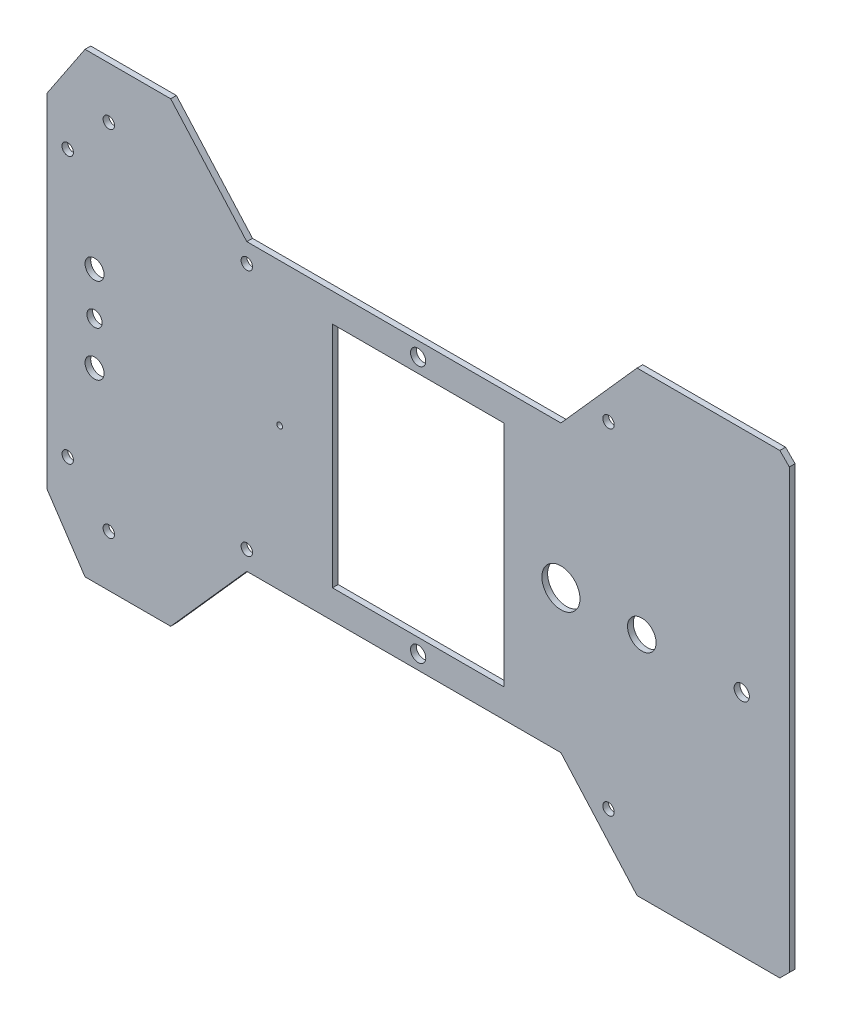
SolidWorks part; units mm, degrees
ref_plane "前视基准面" through (0, 0, 0) normal (0, 0, 1) x (1, 0, 0)
ref_plane "上视基准面" through (0, 0, 0) normal (0, 1, 0) x (1, 0, 0)
ref_plane "右视基准面" through (0, 0, 0) normal (1, 0, 0) x (0, 0, -1)
other "Configuration Table"
sketch "草图1" plane through (0, 0, 0) normal (0, 0, 1) x (1, 0, 0)
  line L0 (0, 0) -> (177289.5009, 0) construction
  line L1 (195, 115) -> (190, 115)
  line L2 (190, 115) -> (190, 120)
  line L3 (0, 0) -> (0, 177289.5009) construction
  line L4 (-175, 120) -> (-175, 90)
  line L5 (-195, 120) -> (195, 120)
  line L6 (-195, 120) -> (-195, -120)
  line L7 (-195, -120) -> (195, -120)
  line L8 (195, 120) -> (195, -120)
  line L9 (-45, 60) -> (45, 60)
  line L10 (-45, 60) -> (-45, -60)
  line L11 (-45, -60) -> (45, -60)
  line L12 (45, 60) -> (45, -60)
  line L13 (-175, 90) -> (-195, 90)
  line L14 (-175, 120) -> (-195, 90)
  line L15 (-175, 120) -> (-130, 120)
  line L16 (190, 120) -> (195, 115)
  line L17 (190, 120) -> (115, 120)
  line L18 (115, 120) -> (115, 75)
  line L19 (115, 75) -> (75, 75)
  line L20 (-130, 120) -> (-130, 75)
  line L21 (-130, 75) -> (-90, 75)
  line L22 (-130, 120) -> (-90, 75)
  line L23 (115, 120) -> (75, 75)
  line L24 (-90, 75) -> (75, 75)
  line L25 (-130, 120) -> (115, 120)
  line L26 (190, -115) -> (190, -120)
  line L27 (195, -115) -> (190, -115)
  line L28 (190, -120) -> (195, -115)
  line L29 (-90, -75) -> (75, -75)
  line L30 (115, -120) -> (115, -75)
  line L31 (115, -75) -> (75, -75)
  line L32 (115, -120) -> (75, -75)
  line L33 (-130, -120) -> (-130, -75)
  line L34 (-130, -75) -> (-90, -75)
  line L35 (-130, -120) -> (-90, -75)
  line L36 (-175, -120) -> (-175, -90)
  line L37 (-175, -90) -> (-195, -90)
  line L38 (-175, -120) -> (-195, -90)
  circle A0 centre (-184.0895, 70) radius 3
  circle A1 centre (104.3795, 93) radius 3
  circle A2 centre (75, 0) radius 10
  circle A3 centre (117.5, 0) radius 7.5
  circle A4 centre (104.3795, -93) radius 3
  circle A5 centre (-184.0895, -70) radius 3
  circle A7 centre (-87, 69) radius 3
  circle A8 centre (-87, -69) radius 3
  point P4 (0, 0)
  point P46 (45, 0)
  dimension "D16" = 6
  dimension "D17" = 6
  dimension "D20" = 20
  dimension "D21" = 30
  dimension "D22" = 42.5
  dimension "D23" = 15
  dimension "D25" = 6
  dimension "D1" = 240
  dimension "D2" = 390
  dimension "D3" = 90
  dimension "D4" = 120
  dimension "D5" = 30
  dimension "D6" = 20
  dimension "D7" = 45
  dimension "D8" = 5
  dimension "D9" = 5
  dimension "D10" = 75
  dimension "D11" = 45
  dimension "D12" = 40
  dimension "D13" = 45
  dimension "D14" = 40
  dimension "D15" = 20
  dimension "D18" = 27
  dimension "D19" = 10
  dimension "D24" = 3
  dimension "D26" = 6
extrude "凸台-拉伸2" add sketch "草图1" along normal blind 3 contours L37 L36 L7 L33 L34 L29 L31 L30 L26 L27 L8 L1 L2 L5 L18 L19 L24 L21 L20 L4 L13 L6 A5 A3 A2 A0 L9 L12 L11 L10 A7 A8 | L22 L20 L21 | L4 L14 L13 | L38 L36 L37 | L33 L35 L34 | L32 L30 L31 A4 | L18 L23 L19 A1 | L16 L2 L1 | L26 L28 L27
sketch "草图2" plane through (0, 0, 3) normal (0, 0, 1) x (1, 0, 0)
  circle A0 centre (117.5, 0) radius 7.5
extrude "凸台-拉伸3" add sketch "草图2" against normal blind 10
sketch "草图3" plane through (0, 0, 3) normal (0, 0, 1) x (1, 0, 0)
  line L0 (115, 120) -> (115, -120)
  line L2 (115, 114.3769) -> (110.0017, 114.3769)
  line L3 (115, 120) -> (75, 75) construction
  line L4 (115, -114.375) -> (110, -114.375)
  line L5 (115, -120) -> (75, -75) construction
  line L6 (110, -114.375) -> (115, -120)
  line L7 (115, 120) -> (110.0017, 114.3769)
  line M8 (75, -75) -> (115, -120)
  line M9 (115, -120) -> (190, -120)
  line M10 (190, -120) -> (195, -115)
  line M11 (195, -115) -> (195, 115)
  line M12 (195, 115) -> (190, 120)
  line M13 (190, 120) -> (115, 120)
  line M14 (115, 120) -> (75, 75)
  dimension "D1" = 5
extrude "切除-拉伸1" cut sketch "草图3" against normal blind 10 contours L0 M13 M9 M10 M11 M12 | L0 L4 M8 | L2 L0 M14
sketch "草图4" plane through (0, 0, 3) normal (0, 0, 1) x (1, 0, 0)
  circle A0 centre (75, 0) radius 10
extrude "凸台-拉伸4" add sketch "草图4" against normal blind 3 contours A0
sketch "草图6" plane through (115, 0, 0) normal (1, 0, 0) x (0, 0, -1)
  line L0 (0, 132) -> (0, -132) construction
  line L1 (7, -7.0711) -> (0, -7.0711)
  line L2 (7, -7.0711) -> (7, 7.0711)
  line L3 (7, 7.0711) -> (0, 7.0711)
  line L4 (0, -7.0711) -> (0, 7.0711)
  line L5 (7, 7.0711) -> (0, 7.0711) construction
extrude "切除-拉伸5" cut sketch "草图6" against normal through all
sketch "草图7" plane through (0, 0, 3) normal (0, 0, 1) x (1, 0, 0)
  line L0 (45, 60) -> (45, -60) construction
  line L1 (-45, 60) -> (45, 60)
  line L2 (-45, 60) -> (-45, -60)
  line L3 (-45, -60) -> (45, -60)
  line L4 (45, 60) -> (45, -60)
extrude "凸台-拉伸5" add sketch "草图7" against normal blind 3
sketch "草图8" plane through (0, 0, 3) normal (0, 0, 1) x (1, 0, 0)
  line L0 (0, 0) -> (50000, 0) construction
  line L1 (0, 0) -> (0, 50000) construction
  line L2 (115, 114.3769) -> (115, -114.375) construction
  line L3 (115, 25) -> (105, 25)
  line L4 (115, 25) -> (115, -25)
  line L5 (115, -25) -> (105, -25)
  line L6 (105, 25) -> (105, -25)
extrude "凸台-拉伸6" add sketch "草图8" along normal blind 30
sketch "草图9" plane through (115, 0, 0) normal (1, 0, 0) x (0, 0, -1)
  line L0 (0, 0) -> (50000, 0) construction
  line L1 (-18, -25) -> (-18, 49975) construction
  line L2 (-33, -25) -> (-3, -25) construction
  circle A0 centre (-17.9316, 0) radius 8
  point P7 (-18, -25)
extrude "切除-拉伸6" cut sketch "草图9" against normal blind 30
sketch "草图10" plane through (0, 0, 3) normal (0, 0, 1) x (1, 0, 0)
  line L0 (104.3795, -96) -> (104.3795, 49904) construction
  line L1 (101.3795, -93) -> (50101.3795, -93) construction
  line L2 (104.3795, 93) -> (50104.3795, 93) construction
  circle A2 centre (104.3795, -93) radius 3
  circle A3 centre (104.3795, 93) radius 3
extrude "凸台-拉伸7" add sketch "草图10" against normal blind 3
sketch "草图11" plane through (0, 0, 3) normal (0, 0, 1) x (1, 0, 0)
  line L0 (0, 0) -> (50000, 0) construction
  line L1 (110, -114.375) -> (75, -75) construction
  line L3 (115, -25) -> (115, -114.375) construction
  circle A0 centre (100, -88.073) radius 3
  circle A1 centre (100, 88.073) radius 3
  dimension "D3" = 6
  dimension "D1" = 10
  dimension "D2" = 15
extrude "切除-拉伸7" cut sketch "草图11" against normal blind 3
sketch "草图12" plane through (0, 0, 3) normal (0, 0, 1) x (1, 0, 0)
  line L0 (0, 0) -> (50000, 0) construction
  line L1 (-87, -69) -> (-87, 49931) construction
  circle A0 centre (-87, 69) radius 3
  circle A1 centre (-87, -69) radius 3
extrude "凸台-拉伸8" add sketch "草图12" against normal blind 3
sketch "草图13" plane through (0, 0, 3) normal (0, 0, 1) x (1, 0, 0)
  line L0 (0, 0) -> (50000, 0) construction
  line L1 (105, 25) -> (105, -25) construction
  line L2 (-90, 75) -> (-90, 50075) construction
  line L3 (75, 75) -> (-90, 75) construction
  circle A0 centre (-90, 65) radius 3
  circle A1 centre (-90, -65) radius 3
  point P5 (105, 0)
  dimension "D1" = 6
  dimension "D2" = 10
extrude "切除-拉伸8" cut sketch "草图13" against normal blind 3
sketch "草图14" plane through (0, 0, 3) normal (0, 0, 1) x (1, 0, 0)
  line L0 (-195, 0) -> (49805, 0) construction
  line L1 (-195, 90) -> (-195, -90) construction
  line L2 (-175, 120) -> (-175, -49880) construction
  line L3 (-162.5, 120) -> (-162.5, 85)
  line L4 (-175, 120) -> (-150, 120)
  line L5 (-175, 120) -> (-175, 85)
  line L6 (-175, 85) -> (-150, 85)
  line L7 (-150, 120) -> (-150, 85)
  circle A0 centre (-162.5, 88) radius 3
  circle A1 centre (-162.5, -88) radius 3
  point P4 (-195, 0)
  dimension "D1" = 35
  dimension "D2" = 25
extrude "切除-拉伸9" cut sketch "草图14" against normal blind 10 contours L3 A0 | L3 A0 | A1
sketch "草图15" plane through (0, 0, 3) normal (0, 0, 1) x (1, 0, 0)
  line L0 (-162.5, -88) -> (-162.5, 49912) construction
  line L1 (-195, 0) -> (49805, 0) construction
  line L2 (-195, 90) -> (-195, -90) construction
  line L3 (-175, -120) -> (-130, -120) construction
  circle A0 centre (-162.5, 88) radius 3
  circle A1 centre (-162.5, -88) radius 3
  circle A2 centre (-162.5, -93) radius 3
  circle A3 centre (-162.5, 93) radius 3
  point P14 (-195, 0)
  circle M3 centre (-162.5, -88) radius 3
  circle M28 centre (-162.5, 88) radius 3
  dimension "D1" = 6
  dimension "D2" = 27
extrude "切除-拉伸10" cut sketch "草图15" against normal through all contours A2 M3 | A3 M28
sketch "草图16" plane through (0, 0, 3) normal (0, 0, 1) x (1, 0, 0)
  line L0 (-162.5, 88) -> (-162.5, 50088) construction
  line L1 (-195, 0) -> (49805, 0) construction
  line L2 (-195, 90) -> (-195, -90) construction
  circle A0 centre (-162.5, 88) radius 3
  circle A1 centre (-162.5, -88) radius 3
  point P7 (-195, 0)
extrude "凸台-拉伸10" add sketch "草图16" against normal blind 3
sketch "草图17" plane through (0, 0, 3) normal (0, 0, 1) x (1, 0, 0)
  line L0 (-162.5, 93) -> (-162.5, 50093) construction
  line L1 (-195, 0) -> (49805, 0) construction
  line L2 (-195, 90) -> (-195, -90) construction
  circle A0 centre (-162.5, 93) radius 3
  circle A1 centre (-162.5, -93) radius 3
  point P7 (-195, 0)
extrude "切除-拉伸11" cut sketch "草图17" against normal through all
sketch "草图18" plane through (0, 0, 3) normal (0, 0, 1) x (1, 0, 0)
  line L0 (-195, 0) -> (49805, 0) construction
  line L1 (-195, 90) -> (-195, -90) construction
  line L2 (-180, 30) -> (-180, -30)
  line L3 (-195, 30) -> (-150, 30)
  line L4 (-195, 30) -> (-195, -30)
  line L5 (-195, -30) -> (-150, -30)
  line L6 (-150, 30) -> (-150, -30)
  circle A0 centre (-170, 22.5) radius 5
  circle A1 centre (-170, -22.5) radius 5
  point P4 (-195, 0)
  dimension "D2" = 7.5
  dimension "D1" = 15
  dimension "D3" = 10
extrude "切除-拉伸12" cut sketch "草图18" against normal blind 10 contours A0 | A1
sketch "草图19" plane through (105, 0, 0) normal (-1, 0, 0) x (0, 0, 1)
  line L1 (33, -25) -> (3, -25)
  line L2 (33, -25) -> (33, 25)
  line L3 (33, 25) -> (3, 25)
  line L4 (3, -25) -> (3, 25)
extrude "切除-拉伸13" cut sketch "草图19" against normal blind 10
sketch "草图20" plane through (0, 0, 3) normal (0, 0, 1) x (1, 0, 0)
  line L0 (115, 114.3769) -> (115, 131.7211)
  line L1 (75, 75) -> (110.0017, 114.3769)
  line L2 (110.0017, 114.3769) -> (115, 120)
  line L3 (115, 0.0009) -> (50115, 0.0009) construction
  line L4 (115, 114.3769) -> (115, -114.375) construction
  line L5 (115, 120) -> (195, 120)
  line L6 (195, 120) -> (195, -119.9981)
  line L7 (115, -119.9981) -> (195, -119.9981)
  line L8 (115, -114.375) -> (115, -131.7192)
  line L9 (110.0017, -114.375) -> (115, -119.9981)
  line L10 (110.0017, 114.3769) -> (115, 114.3769)
  line L11 (110.0017, -114.375) -> (115, -114.375)
  line L12 (115, 114.3769) -> (115, -114.375)
  point P12 (115, 0.0009)
  point P16 (195, 0.0009)
  line M14 (115, -114.375) -> (115, 114.3769)
extrude "凸台-拉伸11" add sketch "草图20" against normal blind 3 contours L3 L8 L7 L6 M14 | L12 L3 L6 L5 L0
sketch "草图21" plane through (0, 0, 3) normal (0, 0, 1) x (1, 0, 0)
  line L0 (115, 120) -> (110.0017, 114.3769)
  line L1 (110.0017, 114.3769) -> (115, 114.3769)
  line L2 (115, 114.3769) -> (115, 120)
  line L3 (110, -114.375) -> (115, -119.9981)
  line L4 (115, -119.9981) -> (115, -114.375)
  line L5 (115, -114.375) -> (110, -114.375)
extrude "凸台-拉伸12" add sketch "草图21" against normal blind 3
sketch "草图22" plane through (0, 0, 3) normal (0, 0, 1) x (1, 0, 0)
  line L0 (195, 115) -> (195, 120)
  line L1 (195, 120) -> (195, -119.9981) construction
  line L2 (195, 120) -> (190, 120)
  line L3 (115, 120) -> (195, 120) construction
  line L4 (190, 120) -> (195, 115)
  line L5 (0, 0) -> (50000, 0) construction
  line L6 (195, -120) -> (190, -120)
  line L7 (195, -115) -> (195, -120)
  line L8 (190, -120) -> (195, -115)
extrude "切除-拉伸14" cut sketch "草图22" against normal blind 3
sketch "草图23" plane through (0, 0, 3) normal (0, 0, 1) x (1, 0, 0)
  line L0 (0, 0) -> (50000, 0) construction
  line L1 (0, 0) -> (0, 50000) construction
  line L3 (-45, 60) -> (45, 60)
  line L4 (-45, 60) -> (-45, -60)
  line L5 (-45, -60) -> (45, -60)
  line L6 (45, 60) -> (45, -60)
  circle A0 centre (79.2237, 0) radius 16.3982
  circle A1 centre (124.3753, 0) radius 14.0564
extrude "切除-拉伸15" cut sketch "草图23" against normal blind 3 contours L6 L3 L4 L5
sketch "草图24" plane through (0, 0, 3) normal (0, 0, 1) x (1, 0, 0)
  line L0 (0, 0) -> (50000, 0) construction
  line L1 (0, 0) -> (0, 50000) construction
  circle A0 centre (75, 0) radius 10
  circle A1 centre (117.5, 0) radius 7.5
  dimension "D1" = 75
  dimension "D2" = 42.5
extrude "切除-拉伸16" cut sketch "草图24" against normal blind 3
sketch "草图25" plane through (0, 0, 3) normal (0, 0, 1) x (1, 0, 0)
  line L0 (-195, 0) -> (49805, 0) construction
  line L1 (-195, 90) -> (-195, -90) construction
  line L2 (-45, 60) -> (-45, -60) construction
  circle A0 centre (-72.75, 0) radius 1.5
  point P4 (-195, 0)
  dimension "D1" = 3
  dimension "D2" = 27.75
extrude "切除-拉伸17" cut sketch "草图25" against normal blind 10
sketch "草图26" plane through (0, 0, 3) normal (0, 0, 1) x (1, 0, 0)
  line L0 (-195, 0) -> (49805, 0) construction
  line L1 (-195, 90) -> (-195, -90) construction
  line L2 (-170, 22.5) -> (-170, 50022.5) construction
  circle A0 centre (-170, 0) radius 4
  point P4 (-195, 0)
extrude "切除-拉伸18" cut sketch "草图26" against normal blind 10
sketch "草图27" plane through (0, 0, 3) normal (0, 0, 1) x (1, 0, 0)
  line L0 (0, 0) -> (0, 50000) construction
  line L1 (0, 0) -> (50000, 0) construction
  line L2 (-45, -60) -> (45, -60) construction
  circle A0 centre (0, -67.5) radius 4
  circle A1 centre (0, 67.5) radius 4
  circle A2 centre (-170, 0) radius 4
  circle A3 centre (170, 0) radius 4
  dimension "D1" = 7.5
extrude "切除-拉伸19" cut sketch "草图27" against normal blind 10
